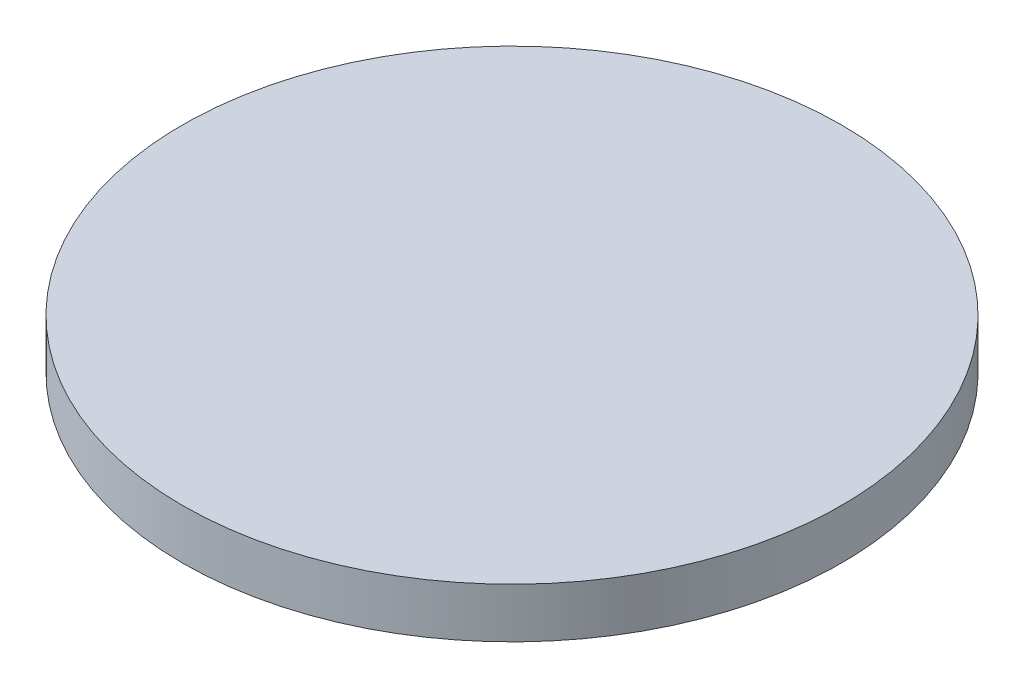
SolidWorks part; units mm, degrees
ref_plane "Alzado" through (0, 0, 0) normal (0, 0, 1) x (1, 0, 0)
ref_plane "Planta" through (0, 0, 0) normal (0, 1, 0) x (1, 0, 0)
ref_plane "Vista lateral" through (0, 0, 0) normal (1, 0, 0) x (0, 0, -1)
sketch "Croquis1" plane through (0, 0, 0) normal (0, 1, 0) x (1, 0, 0)
  circle A0 centre (0, 0) radius 33
  dimension "D1" = 66
extrude "Saliente-Extruir1" add sketch "Croquis1" along normal blind 5
